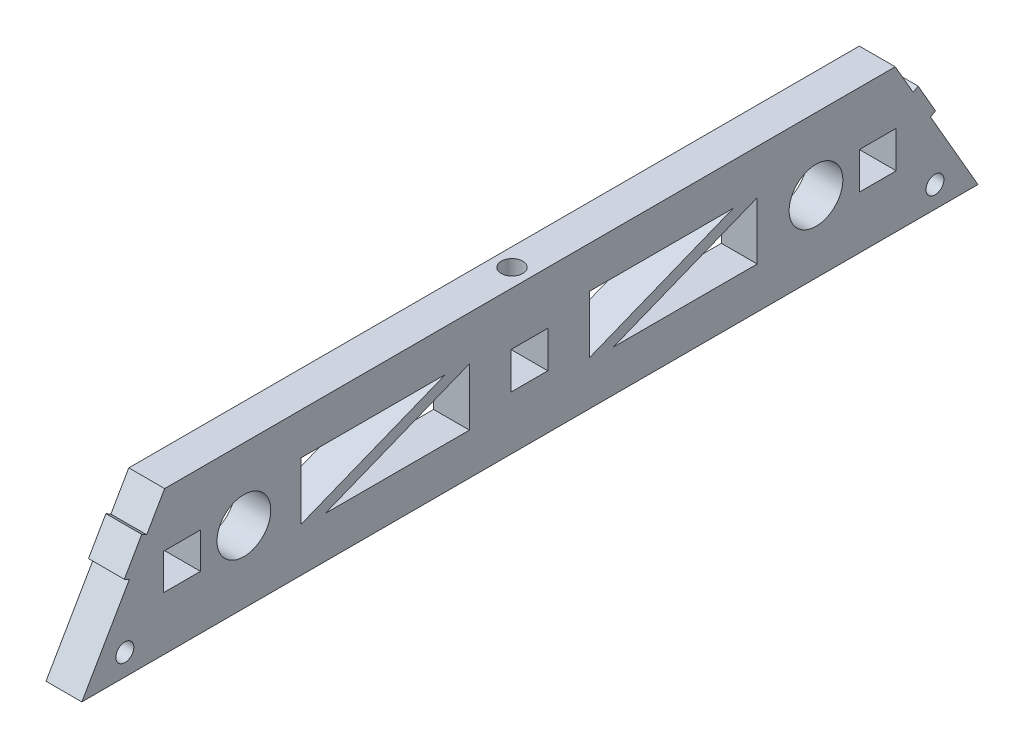
SolidWorks part; units mm, degrees
material "6061-T6 (SS)"
ref_plane "Front Plane" through (0, 0, 0) normal (0, 0, 1) x (1, 0, 0)
ref_plane "Top Plane" through (0, 0, 0) normal (0, 1, 0) x (1, 0, 0)
ref_plane "Right Plane" through (0, 0, 0) normal (1, 0, 0) x (0, 0, -1)
sketch "Sketch1" plane through (0, 0, 0) normal (1, 0, 0) x (0, 0, -1)
  line L0 (0, 0) -> (-14.6647, 25.4)
  line L1 (0, 0) -> (-158.75, 0)
  line L2 (-79.375, 25.4) -> (-79.375, 0.0032) construction
  line L3 (-14.6647, 25.4) -> (-144.0853, 25.4)
  line L4 (-21.0147, 9.3472) -> (-14.4869, 9.3472)
  line L5 (-158.75, 0) -> (-144.0853, 25.4)
  line L6 (-21.0147, 9.3472) -> (-21.0147, 15.875)
  line L7 (-21.0147, 15.875) -> (-14.4869, 15.875)
  line L8 (-14.4869, 9.3472) -> (-14.4869, 15.875)
  line L9 (-144.2631, 9.5262) -> (-144.2631, 15.875)
  line L10 (-137.7353, 15.875) -> (-144.2631, 15.875)
  line L11 (-137.7353, 9.5262) -> (-137.7353, 15.875)
  line L12 (-137.7353, 9.5262) -> (-144.2631, 9.5262)
  line L14 (-76.2, 16.0528) -> (-82.7278, 16.0528)
  line L15 (-76.2, 16.0528) -> (-76.2, 9.525)
  line L16 (-76.2, 9.525) -> (-82.7278, 9.525)
  line L17 (-82.7278, 16.0528) -> (-82.7278, 9.525)
  circle A0 centre (-130.048, 12.7) radius 4.7625
  circle A1 centre (-28.702, 12.7) radius 4.7625
  dimension "D3" = 9.525
  dimension "D5" = 9.525
  dimension "D9" = 60
  dimension "D12" = 6.5278
  dimension "D2" = 28.702
  dimension "D4" = 12.7
  dimension "D6" = 28.702
  dimension "D7" = 25.4
  dimension "D8" = 12.7
  dimension "D10" = 60
  dimension "D11" = 129.4206
  dimension "D13" = 6.5278
  dimension "D14" = 9.525
  dimension "D15" = 6.35
  dimension "D16" = 6.35
  dimension "D17" = 76.2
  dimension "D18" = 9.525
  dimension "D19" = 6.5278
  dimension "D20" = 6.5278
  dimension "D21" = 6.5278
  dimension "D22" = 6.3488
extrude "Boss-Extrude1" add sketch "Sketch1" along normal blind 6.35
hole_wizard "#6 Clearance Hole1" positions "Sketch6" profile "Sketch5" hole size "#6" standard "ANSI Inch"
sketch "Sketch6" plane through (0, 25.4, 0) normal (0, 1, 0) x (1, 0, 0)
  line L0 (6.35, 0) -> (0, 0) construction
  line L1 (0, -14.6647) -> (0, -144.0853) construction
  point P39 (3.175, -79.375)
  dimension "D1" = 79.375
  dimension "D2" = 3.175
sketch "Sketch5" plane through (3.175, 25.4, 79.375) normal (1, 0, 0) x (0, 0, 1)
  line L0 (0, 0) -> (0, 13.8408)
  line L1 (0, 13.8408) -> (1.8986, 12.7)
  line L2 (1.8986, 12.7) -> (1.8986, 0)
  line L5 (1.8986, 0) -> (0, 0)
  line L10 (0, 13.8408) -> (-1.8987, 12.7) construction
  line L11 (0, -6.35) -> (0, 107.95) construction
  dimension "Hole Dia." = 3.7973
  dimension "Hole Depth" = 12.7
  dimension "Drill Angle" = 118
sketch "Sketch7" plane through (0, 0, 0) normal (0, 0.5, -0.866) x (-1, 0, 0)
  line L0 (-6.35, 0) -> (-6.35, 29.3294) construction
  line L1 (-6.35, 22.9794) -> (0, 22.9794)
  line L2 (-6.35, 22.9794) -> (-6.35, 16.8072)
  line L3 (-6.35, 16.8072) -> (0, 16.8072)
  line L4 (0, 22.9794) -> (0, 16.8072)
  line L5 (0, 0) -> (0, 29.3294) construction
  line L6 (-6.35, 29.3294) -> (0, 29.3294) construction
  dimension "D1" = 6.1722
  dimension "D2" = 6.35
extrude "Boss-Extrude2" add sketch "Sketch7" along normal blind 1.016
sketch "Sketch8" plane through (0, 68.7408, 119.0625) normal (0, 0.5, 0.866) x (1, 0, 0)
  line L0 (0, -50.0456) -> (0, -79.375) construction
  line L1 (6.35, -50.0456) -> (6.35, -79.375) construction
  line L2 (0, -56.3956) -> (6.35, -56.3956)
  line L3 (0, -56.3956) -> (0, -62.5678)
  line L4 (0, -62.5678) -> (6.35, -62.5678)
  line L5 (6.35, -56.3956) -> (6.35, -62.5678)
  line L6 (6.35, -50.0456) -> (0, -50.0456) construction
  dimension "D1" = 6.1722
  dimension "D2" = 6.35
extrude "Boss-Extrude3" add sketch "Sketch8" along normal blind 1.016
sketch "Sketch9" plane through (6.35, 0, 0) normal (1, 0, 0) x (0, 0, -1)
  line L0 (-14.6647, 25.4) -> (-144.0853, 25.4) construction
  circle A0 centre (-151.13, 3.81) radius 1.5875
  circle A1 centre (-7.62, 3.81) radius 1.5875
  dimension "D1" = 3.175
  dimension "D4" = 3.175
  dimension "D2" = 21.59
  dimension "D3" = 7.62
  dimension "D5" = 21.59
  dimension "D6" = 7.62
extrude "Cut-Extrude1" cut sketch "Sketch9" against normal through all
sketch "Sketch10" plane through (6.35, 0, 0) normal (1, 0, 0) x (0, 0, -1)
  line L0 (-82.7278, 16.0528) -> (-82.7278, 9.525) construction
  line L1 (-120.9176, 19.05) -> (-89.0778, 19.05)
  line L2 (-120.9176, 19.05) -> (-120.9176, 6.35)
  line L3 (-120.9176, 6.35) -> (-89.0778, 6.35)
  line L4 (-89.0778, 19.05) -> (-89.0778, 6.35)
  line L5 (-14.6647, 25.4) -> (-144.0853, 25.4) construction
  line L6 (-120.9176, 6.35) -> (-89.0778, 19.05)
  line L7 (-158.75, 0) -> (0, 0) construction
  line L8 (-76.2, 9.525) -> (-76.2, 16.0528) construction
  line L9 (-69.85, 19.05) -> (-38.1, 19.05)
  line L10 (-69.85, 19.05) -> (-69.85, 6.35)
  line L11 (-69.85, 6.35) -> (-38.1, 6.35)
  line L12 (-38.1, 19.05) -> (-38.1, 6.35)
  line L13 (-89.0778, 19.05) -> (-88.856, 19.3169)
  line L14 (-69.85, 6.35) -> (-38.1, 19.05)
  line L15 (-119.9016, 18.034) -> (-119.9016, 6.35)
  line L16 (-119.9016, 18.034) -> (-89.0778, 18.034)
  line L17 (-121.9336, 20.066) -> (-121.9336, 6.35)
  line L18 (-121.9336, 20.066) -> (-89.0778, 20.066)
  line L19 (-120.5412, 5.4063) -> (-88.7014, 18.1063)
  line L20 (-120.9176, 5.334) -> (-88.0618, 5.334)
  line L21 (-88.0618, 19.05) -> (-88.0618, 5.334)
  line L22 (-70.866, 20.066) -> (-38.1, 20.066)
  line L23 (-70.866, 20.066) -> (-70.866, 6.35)
  line L24 (-69.4727, 5.4067) -> (-37.7227, 18.1067)
  line L25 (-69.85, 5.334) -> (-37.084, 5.334)
  line L26 (-37.084, 19.05) -> (-37.084, 5.334)
  line L27 (-121.294, 7.2937) -> (-89.4542, 19.9937)
  line L28 (-120.9176, 7.366) -> (-90.0938, 7.366)
  line L29 (-90.0938, 19.05) -> (-90.0938, 7.366)
  line L30 (-68.834, 18.034) -> (-38.1, 18.034)
  line L31 (-68.834, 18.034) -> (-68.834, 6.35)
  line L32 (-70.2273, 7.2933) -> (-38.4773, 19.9933)
  line L33 (-69.85, 7.366) -> (-39.116, 7.366)
  line L34 (-39.116, 19.05) -> (-39.116, 7.366)
  dimension "D1" = 6.35
  dimension "D2" = 6.35
  dimension "D3" = 6.35
  dimension "D4" = 31.8398
  dimension "D5" = 6.35
  dimension "D6" = 38.1
  dimension "D7" = 6.35
  dimension "D8" = 6.35
  dimension "D9" = 1.016
  dimension "D10" = 1.016
  dimension "D11" = 1.016
  dimension "D12" = 1.016
extrude "Cut-Extrude2" cut sketch "Sketch10" against normal through all contours L29 L19 L28 | L15 L27 L16 | L31 L32 L30 | L34 L24 L33
equation "\"D8@Sketch1\"=\"D4@Sketch1\""
